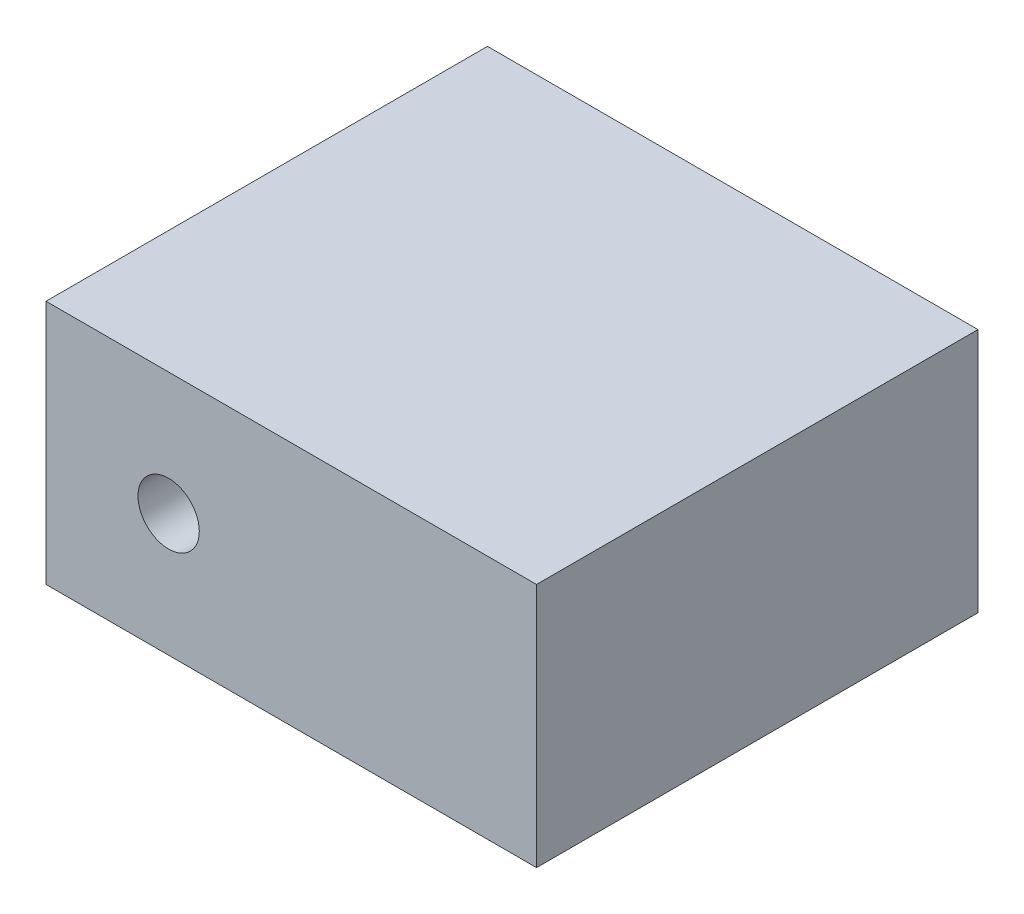
SolidWorks part; units mm, degrees
ref_plane "Plan de face" through (0, 0, 0) normal (0, 0, 1) x (1, 0, 0)
ref_plane "Plan de dessus" through (0, 0, 0) normal (0, 1, 0) x (1, 0, 0)
ref_plane "Plan de droite" through (0, 0, 0) normal (1, 0, 0) x (0, 0, -1)
sketch "Esquisse1" plane through (0, 0, 0) normal (0, 0, 1) x (1, 0, 0)
  line L1 (0, 0) -> (40, 0)
  line L2 (0, 0) -> (0, 20)
  line L3 (0, 20) -> (40, 20)
  line L4 (40, 0) -> (40, 20)
  dimension "D1" = 40
  dimension "D2" = 20
extrude "Boss.-Extru.1" add sketch "Esquisse1" along normal mid plane 36
sketch "Esquisse2" plane through (0, 0, 18) normal (0, 0, 1) x (1, 0, 0)
  line L0 (0, 20) -> (0, 0) construction
  line L1 (0, 0) -> (40, 0) construction
  circle A0 centre (10, 10) radius 2.5
  point P2 (0, 0)
  dimension "D1" = 5
  dimension "D2" = 10
  dimension "D3" = 10
extrude "Enlèv. mat.-Extru.1" cut sketch "Esquisse2" against normal blind 10
